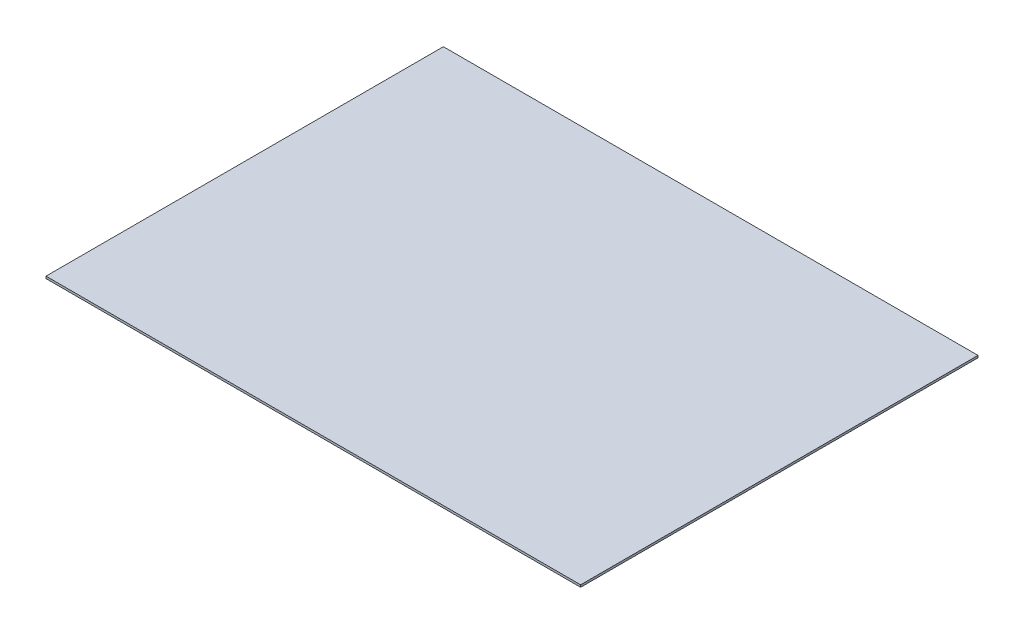
SolidWorks part; units mm, degrees
material "Malleable Cast Iron"
ref_plane "Front Plane" through (0, 0, 0) normal (0, 0, 1) x (1, 0, 0)
ref_plane "Top Plane" through (0, 0, 0) normal (0, 1, 0) x (1, 0, 0)
ref_plane "Right Plane" through (0, 0, 0) normal (1, 0, 0) x (0, 0, -1)
sketch "Sketch1" plane through (0, 0, 0) normal (0, 1, 0) x (1, 0, 0)
  line L1 (-233.3874, 191.3777) -> (392.0909, 191.3777)
  line L2 (-233.3874, 191.3777) -> (-233.3874, -273.5301)
  line L3 (-233.3874, -273.5301) -> (392.0909, -273.5301)
  line L4 (392.0909, 191.3777) -> (392.0909, -273.5301)
extrude "Boss-Extrude1" add sketch "Sketch1" along normal blind 2.54
